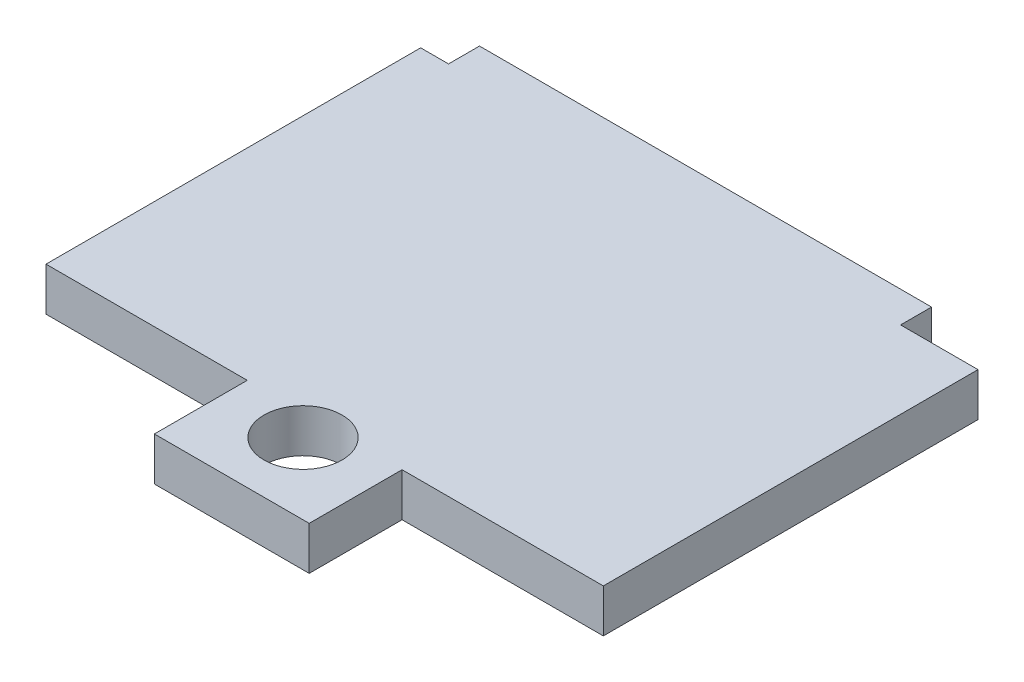
SolidWorks part; units mm, degrees
ref_plane "Front Plane" through (0, 0, 0) normal (0, 0, 1) x (1, 0, 0)
ref_plane "Top Plane" through (0, 0, 0) normal (0, 1, 0) x (1, 0, 0)
ref_plane "Right Plane" through (0, 0, 0) normal (1, 0, 0) x (0, 0, -1)
sketch "Sketch1" plane through (0, 0, 0) normal (0, 1, 0) x (1, 0, 0)
  line L0 (0, 15.367) -> (0, 0)
  line L1 (0, 0) -> (8.255, 0)
  line L2 (8.255, 0) -> (8.255, -3.81)
  line L3 (8.255, -3.81) -> (14.605, -3.81)
  line L4 (14.605, -3.81) -> (14.605, 0)
  line L5 (14.605, 0) -> (22.86, 0)
  line L6 (22.86, 0) -> (22.86, 15.367)
  line L8 (0, 15.367) -> (1.143, 15.367)
  line L9 (1.143, 15.367) -> (1.143, 16.637)
  line L10 (1.143, 16.637) -> (19.685, 16.637)
  line L11 (19.685, 16.637) -> (19.685, 15.367)
  line L12 (19.685, 15.367) -> (22.86, 15.367)
  dimension "D1" = 18.542
  dimension "D2" = 22.86
  dimension "D3" = 1.143
  dimension "D4" = 15.367
  dimension "D5" = 1.27
  dimension "D6" = 3.81
  dimension "D7" = 6.35
  dimension "D8" = 8.255
extrude "Boss-Extrude1" add sketch "Sketch1" along normal blind 1.778
hole_wizard "M3 Clearance Hole1" positions "Sketch2" profile "Sketch3" hole size "M3" standard "ANSI Metric" end condition through all
sketch "Sketch2" plane through (0, 1.778, 0) normal (0, 1, 0) x (1, 0, 0)
  line L0 (8.255, -3.81) -> (14.605, -3.81) construction
  line L1 (23.2514, 2.0338) -> (23.2514, -3.81) construction
  line L2 (12.3825, 2.0338) -> (23.495, 2.0338) construction
  point P0 (11.43, -0.8881)
  point P5 (11.43, -3.81)
  point P13 (23.2514, -0.8881)
sketch "Sketch3" plane through (11.43, 1.778, 0.8881) normal (1, 0, 0) x (0, 0, 1)
  line L0 (0, 0) -> (0, 1.778)
  line L1 (0, 1.778) -> (1.6, 1.778)
  line L2 (1.6, 1.778) -> (1.6, 0)
  line L5 (1.6, 0) -> (0, 0)
  line L11 (0, -6.35) -> (0, 107.95) construction
  dimension "Thru Hole Dia." = 3.2
  dimension "Thru Hole Depth" = 1.778
sketch "Sketch4" plane through (0, 0, 0) normal (0, -1, 0) x (1, 0, 0)
  line L1 (15.24, -4.3028) -> (17.78, -4.3028)
  line L2 (15.24, -4.3028) -> (15.24, -13.4468)
  line L3 (15.24, -13.4468) -> (17.78, -13.4468)
  line L4 (17.78, -4.3028) -> (17.78, -13.4468)
  line L5 (0, -4.3028) -> (2.54, -4.3028)
  line L6 (0, -4.3028) -> (0, -13.4468)
  line L7 (0, -13.4468) -> (2.54, -13.4468)
  line L8 (2.54, -4.3028) -> (2.54, -13.4468)
  line L9 (22.86, 0) -> (22.86, -15.367) construction
  line L10 (-0.635, -12.8914) -> (23.495, -12.8914) construction
  dimension "D1" = 9.144
  dimension "D2" = 2.54
  dimension "D3" = 12.7
  dimension "D4" = 5.08
  dimension "D5" = 0.5554
extrude "Boss-Extrude2" add sketch "Sketch4" along normal blind 0.508
sketch "Sketch5" plane through (0, 0, 0) normal (0, -1, 0) x (1, 0, 0)
  text T0 "<b>20</b>"
  point P1 (6.3856, -10.0168)
extrude "Cut-Extrude1" cut sketch "Sketch5" against normal blind 0.508
